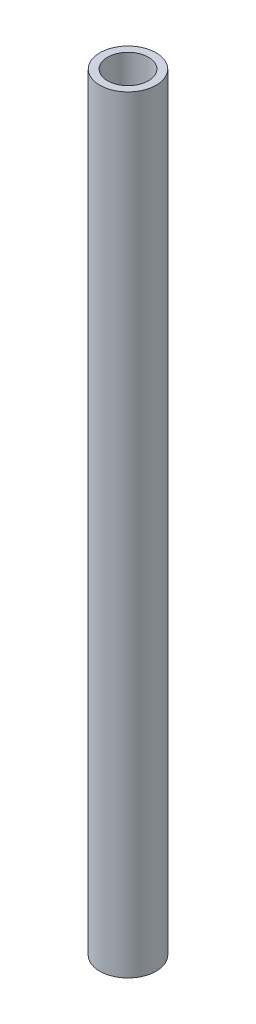
SolidWorks part; units mm, degrees
ref_plane "前视" through (0, 0, 0) normal (0, 0, 1) x (1, 0, 0)
ref_plane "上视" through (0, 0, 0) normal (0, 1, 0) x (1, 0, 0)
ref_plane "右视" through (0, 0, 0) normal (1, 0, 0) x (0, 0, -1)
sketch "草图1" plane through (0, 0, 0) normal (0, 1, 0) x (1, 0, 0)
  circle A0 centre (0, 0) radius 4
  circle A1 centre (0, 0) radius 5.5
  dimension "D1" = 8
  dimension "D2" = 11
extrude "凸台-拉伸1" add sketch "草图1" along normal blind 150
